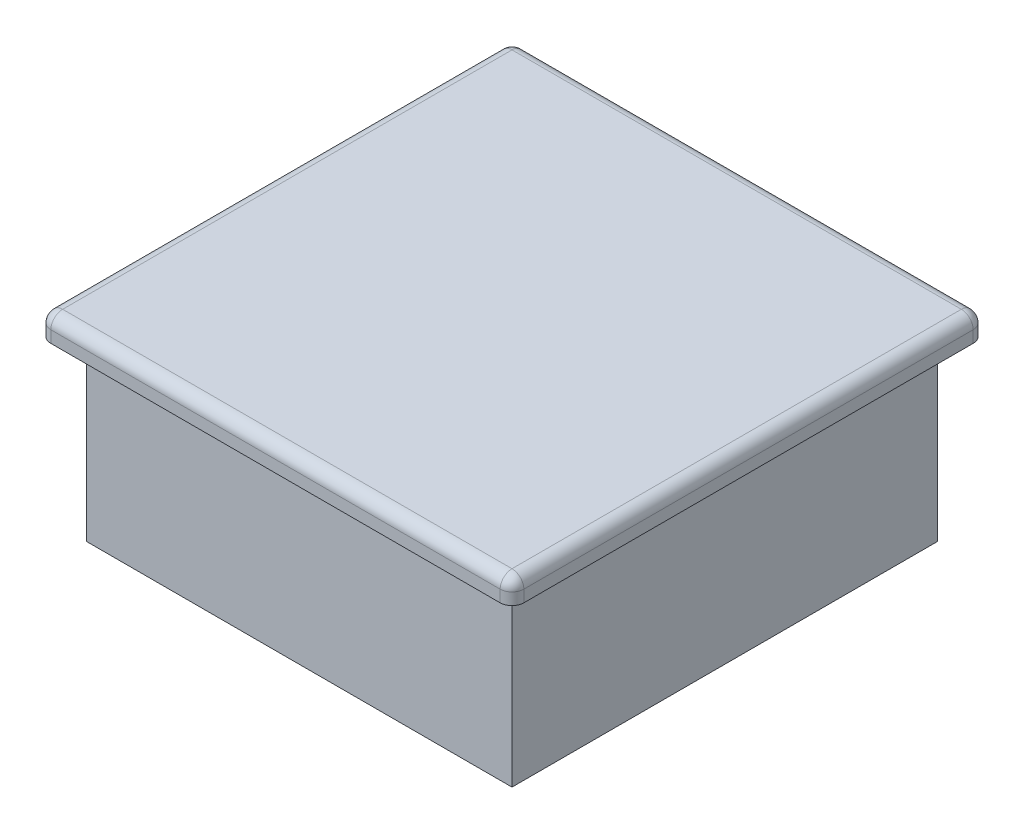
SolidWorks part; units mm, degrees
ref_plane "Front Plane" through (0, 0, 0) normal (0, 0, 1) x (1, 0, 0)
ref_plane "Top Plane" through (0, 0, 0) normal (0, 1, 0) x (1, 0, 0)
ref_plane "Right Plane" through (0, 0, 0) normal (1, 0, 0) x (0, 0, -1)
sketch "Sketch1" plane through (0, 0, 0) normal (0, 1, 0) x (1, 0, 0)
  line L1 (-20, 20) -> (20, 20)
  line L2 (-20, 20) -> (-20, -20)
  line L3 (-20, -20) -> (20, -20)
  line L4 (20, 20) -> (20, -20)
  line L5 (-20, 20) -> (20, -20) construction
  line L6 (-20, -20) -> (20, 20) construction
  line L11 (-11, 14) -> (11, -14) construction
  line L12 (-11, -14) -> (11, 14) construction
  point P0 (0, 0)
  point P6 (0, 0)
  dimension "D1" = 40
  dimension "D2" = 28
  dimension "D3" = 22
extrude "Boss-Extrude1" add sketch "Sketch1" along normal blind 2
sketch "Sketch2" plane through (0, 0, 0) normal (0, -1, 0) x (-1, 0, 0)
  line L1 (-20, 20) -> (20, 20)
  line L2 (-20, 20) -> (-20, -20)
  line L3 (-20, -20) -> (20, -20)
  line L4 (20, 20) -> (20, -20)
  line L5 (18, -18) -> (-18, -18)
  line L6 (18, -18) -> (18, 18)
  line L7 (18, 18) -> (-18, 18)
  line L8 (-18, -18) -> (-18, 18)
  line L9 (-16, 16) -> (16, 16)
  line L10 (-16, 16) -> (-16, -16)
  line L11 (-16, -16) -> (16, -16)
  line L12 (16, 16) -> (16, -16)
  dimension "D1" = 2
  dimension "D2" = 2
  dimension "D3" = 2
  dimension "D4" = 2
  dimension "D5" = 2
  dimension "D6" = 2
  dimension "D7" = 2
  dimension "D8" = 2
extrude "Boss-Extrude2" add sketch "Sketch2" along normal blind 15 contours L8 L5 L6 L7 L9 L12 L11 L10
fillet "Fillet1" radius 1 8 edges at (-20, 1, 20) (20, 2, 0) (0, 2, 20) (-20, 2, 0) (0, 2, -20) (-20, 1, -20) (20, 1, -20) (20, 1, 20)
